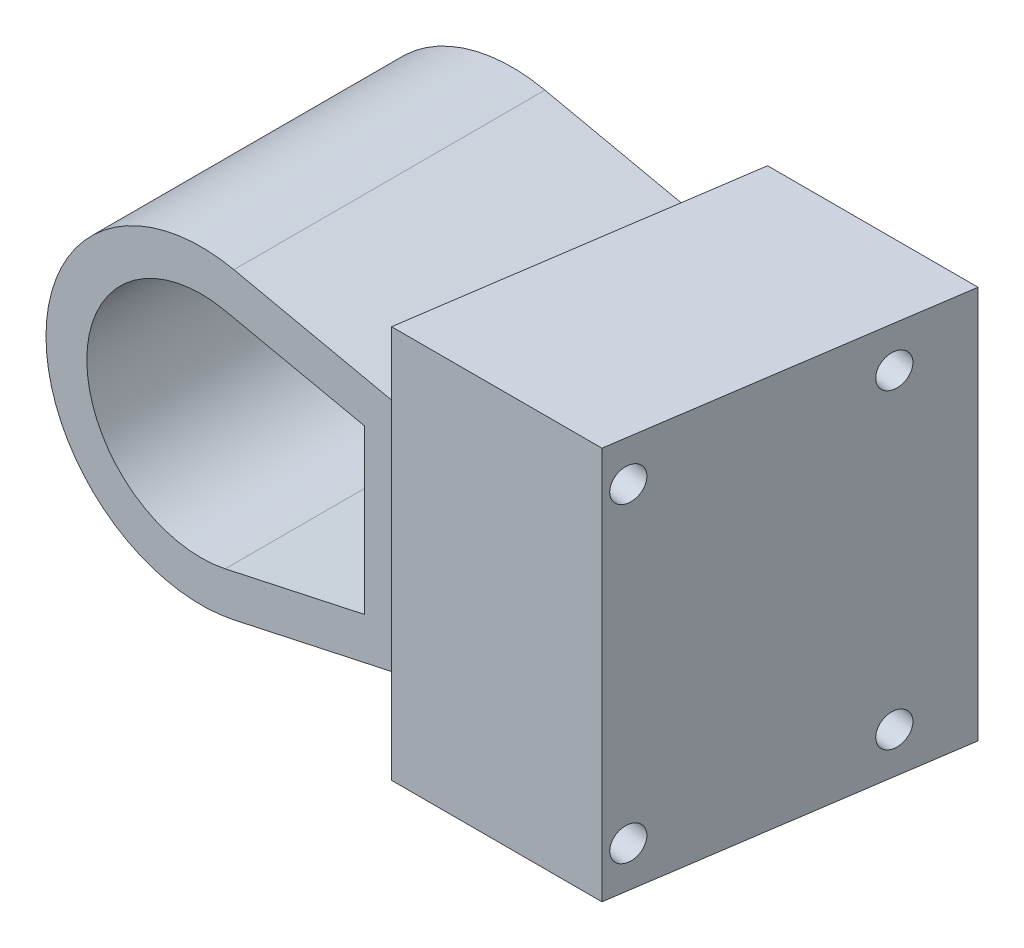
SolidWorks part; units mm, degrees
material "6061-T6 (SS)"
ref_plane "Front Plane" through (0, 0, 0) normal (0, 0, 1) x (1, 0, 0)
ref_plane "Top Plane" through (0, 0, 0) normal (0, 1, 0) x (1, 0, 0)
ref_plane "Right Plane" through (0, 0, 0) normal (1, 0, 0) x (0, 0, -1)
sketch "Sketch1" plane through (0, 0, 0) normal (0, 0, 1) x (1, 0, 0)
  line L0 (17.6441, -10.101) -> (17.6441, 9.8497)
  line L1 (17.6441, 9.8497) -> (0.6444, 13.5248)
  line L2 (0.6444, -13.7761) -> (17.6441, -10.101)
  line L3 (22.6317, -14.1257) -> (22.6317, 13.8743)
  line L4 (22.6317, 13.8743) -> (1.6983, 18.3999)
  line L5 (1.6983, -18.6512) -> (22.6317, -14.1257)
  arc A0 (0.6444, 13.5248) -> (-2.3067, 13.8402) centre (-2.3067, -0.1257) ccw
  arc A1 (-2.3067, 13.8402) -> (-2.3067, -14.0915) centre (-2.3067, -0.1257) ccw
  arc A2 (-2.3067, -14.0915) -> (0.6444, -13.7761) centre (-2.3067, -0.1257) ccw
  arc A3 (1.6983, 18.3999) -> (-2.3067, 18.8278) centre (-2.3067, -0.1257) ccw
  arc A4 (-2.3067, 18.8278) -> (-2.3067, -19.0791) centre (-2.3067, -0.1257) ccw
  arc A5 (-2.3067, -19.0791) -> (1.6983, -18.6512) centre (-2.3067, -0.1257) ccw
  dimension "D1" = 28
extrude "Boss-Extrude1" add sketch "Sketch1" along normal blind 38
sketch "Sketch2" plane through (0, 0, 0) normal (0, 1, 0) x (1, 0, 0)
  line L0 (22.6317, -38) -> (22.6317, 0)
  line L1 (22.6317, 0) -> (48.277, 0)
  line L2 (48.277, 0) -> (42.6317, -38)
  line L3 (42.6317, -38) -> (22.6317, -38)
  dimension "D1" = 81.55
  dimension "D2" = 20
  dimension "D3" = 38
extrude "Boss-Extrude2" add sketch "Sketch2" along normal mid plane 28
sketch "Sketch4" plane through (0, 14, 0) normal (0, 1, 0) x (1, 0, 0)
  line L0 (28.8995, 0) -> (22.9571, -40)
  line L1 (48.277, 0) -> (22.6317, 0) construction
  line L3 (42.6317, -38) -> (48.277, 0) construction
  line L4 (28.8995, 0) -> (54.6085, 0)
  line L5 (54.6085, 0) -> (48.6662, -40)
  line L6 (48.6662, -40) -> (22.9571, -40)
  dimension "D1" = 25.43
extrude "Boss-Extrude5" add sketch "Sketch4" along normal blind 10 and the other way blind 38
sketch "Sketch6" plane through (28.2754, 0, 4.2006) normal (-0.9891, 0, -0.1469) x (-0.1469, 0, 0.9891)
  line L0 (0.9746, 19) -> (29.5831, 19) construction
  line L1 (0.9746, 19) -> (0.9746, -19) construction
  line L2 (29.5831, 19) -> (29.5831, -19) construction
  line L3 (0.9746, -19) -> (29.5831, -19) construction
  line L4 (-4.2467, 24) -> (36.1923, 24) construction
  circle A0 centre (0.9746, 19) radius 2
  circle A1 centre (29.5831, 19) radius 2
  circle A2 centre (0.9746, -19) radius 2
  circle A3 centre (29.5831, -19) radius 2
  point P0 (0.9746, 0)
  dimension "D1" = 4
  dimension "D2" = 5
extrude "Cut-Extrude2" cut sketch "Sketch6" against normal blind 36
